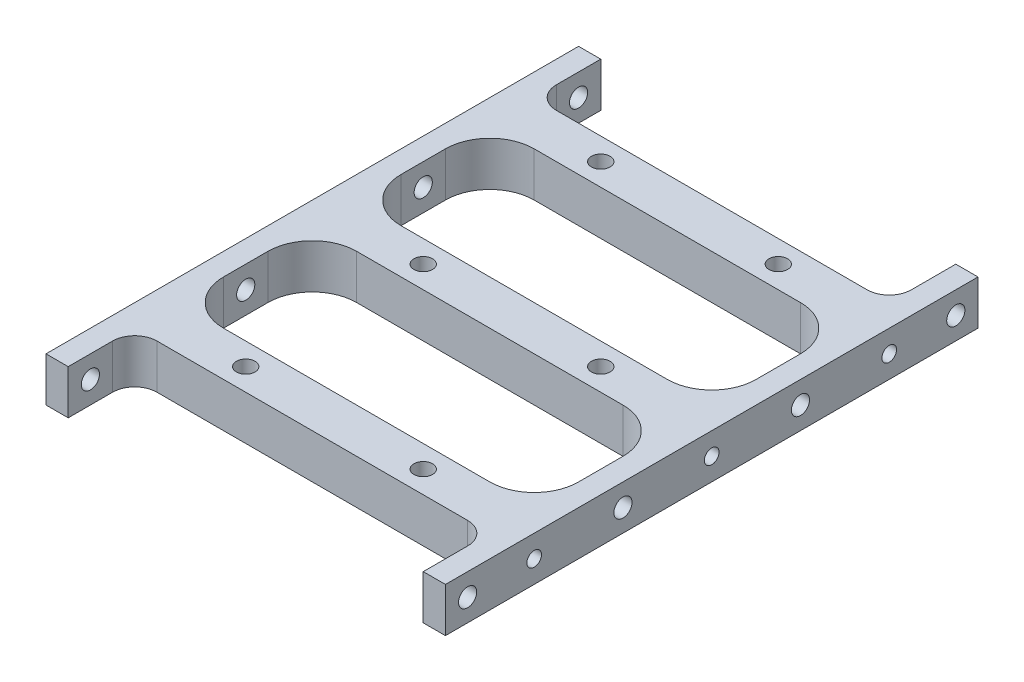
SolidWorks part; units mm, degrees
ref_plane "前视基准面" through (0, 0, 0) normal (0, 0, 1) x (1, 0, 0)
ref_plane "上视基准面" through (0, 0, 0) normal (0, 1, 0) x (1, 0, 0)
ref_plane "右视基准面" through (0, 0, 0) normal (1, 0, 0) x (0, 0, -1)
sketch "草图1" plane through (0, 0, 0) normal (0, 1, 0) x (1, 0, 0)
  line L0 (-45, 60) -> (-40, 60)
  line L1 (-40, 60) -> (-40, 45)
  line L2 (-30, 5) -> (30, 5)
  line L3 (40, 15) -> (40, 25)
  line L4 (40, 60) -> (45, 60)
  line L5 (45, 60) -> (45, -60)
  line L6 (45, -60) -> (40, -60)
  line L7 (40, -60) -> (40, -45)
  line L8 (30, -5) -> (-30, -5)
  line L9 (-40, -15) -> (-40, -25)
  line L10 (-40, -60) -> (-45, -60)
  line L11 (-45, -60) -> (-45, 60)
  line L12 (-45, 0) -> (45, 0) construction
  line L13 (0, 5) -> (0, -5) construction
  line L14 (-40, 45) -> (40, 45)
  line L15 (-30, 35) -> (30, 35)
  line L16 (-45, 40) -> (45, 40) construction
  line L17 (-45, -40) -> (45, -40) construction
  line L18 (-30, -35) -> (30, -35)
  line L19 (-40, -45) -> (40, -45)
  line L20 (-40, 25) -> (-40, 15)
  line L21 (40, 45) -> (40, 60)
  line L22 (40, -25) -> (40, -15)
  line L23 (-40, -45) -> (-40, -60)
  arc A0 (40, -25) -> (30, -35) centre (30, -25) cw
  arc A1 (-40, -25) -> (-30, -35) centre (-30, -25) ccw
  arc A2 (40, -15) -> (30, -5) centre (30, -15) ccw
  arc A3 (-40, -15) -> (-30, -5) centre (-30, -15) cw
  arc A4 (30, 5) -> (40, 15) centre (30, 15) ccw
  arc A5 (40, 25) -> (30, 35) centre (30, 25) ccw
  arc A6 (-40, 15) -> (-30, 5) centre (-30, 15) ccw
  arc A7 (-40, 25) -> (-30, 35) centre (-30, 25) cw
  point P31 (40, -35)
  point P46 (-40, 35)
  dimension "D10" = 10
  dimension "D1" = 90
  dimension "D2" = 10
  dimension "D3" = 5
  dimension "D4" = 5
  dimension "D5" = 120
  dimension "D6" = 40
  dimension "D7" = 10
  dimension "D8" = 40
  dimension "D9" = 10
extrude "凸台-拉伸1" add sketch "草图1" along normal mid plane 10
sketch "草图2" plane through (-45, 0, 0) normal (-1, 0, 0) x (0, 0, 1)
  line L0 (-55, 0) -> (55, 0) construction
  line L1 (-60, 5) -> (-60, -5) construction
  line L2 (60, 5) -> (60, -5) construction
  circle A0 centre (-55, 0) radius 2.05
  circle A1 centre (55, 0) radius 2.05
  circle A2 centre (-20, 0) radius 2.05
  circle A3 centre (20, 0) radius 2.05
  dimension "D1" = 5
  dimension "D2" = 35
  dimension "D3" = 5
  dimension "D4" = 35
  dimension "D5" = 4.1
extrude "切除-拉伸1" cut sketch "草图2" against normal through all
hole_wizard "M4 螺纹孔2" positions "草图7" profile "草图6" tap size "M4" standard "GB"
sketch "草图7" plane through (-45, 0, 0) normal (-1, 0, 0) x (0, 0, 1)
  circle A0 centre (-55, 0) radius 2.05 construction
  circle A1 centre (55, 0) radius 2.05 construction
  point P0 (0, 0)
  point P3 (-40, 0)
  point P8 (40, 0)
  dimension "D1" = 15
  dimension "D2" = 15
sketch "草图6" plane through (-45, 0, 0) normal (0, 1, 0) x (0, 0, 1)
  line L0 (0, 0) -> (0, 18.0914)
  line L1 (0, 18.0914) -> (1.65, 17.1)
  line L2 (1.65, 17.1) -> (1.65, 0)
  line L5 (1.65, 0) -> (0, 0)
  line L10 (0, 18.0914) -> (-1.65, 17.1) construction
  line L11 (0, -6.35) -> (0, 107.95) construction
  dimension "螺纹孔钻头直径" = 3.3
  dimension "螺纹孔钻头深度" = 17.1
  dimension "导头角度" = 118
cosmetic thread "孔螺蚊线4" parameters "D1"=12, "D2"=4
cosmetic thread "孔螺蚊线5" parameters "D1"=12, "D2"=4
cosmetic thread "孔螺蚊线6" parameters "D1"=12, "D2"=4
mirror "镜向1" about plane through (0, 0, 0) normal (1, 0, 0) of "M4 螺纹孔2"
fillet "圆角1" radius 5 4 edges at (-40, 0, 45) (40, 0, 45) (-40, 0, -45) (40, 0, -45)
hole_wizard "M5 螺纹孔1" positions "草图10" profile "草图9" tap size "M5" standard "GB" end condition through all
sketch "草图10" plane through (0, 5, 0) normal (0, 1, 0) x (1, 0, 0)
  line L0 (-20, 40) -> (20, 40) construction
  line L1 (20, 40) -> (20, 0) construction
  line L2 (20, 0) -> (20, -40) construction
  line L3 (20, -40) -> (-20, -40) construction
  line L4 (-20, -40) -> (-20, 0) construction
  line L5 (-20, 0) -> (-20, 40) construction
  line L7 (0, 0) -> (0, 40) construction
  point P2 (20, 40)
  point P4 (20, 0)
  point P6 (20, -40)
  point P8 (-20, -40)
  point P10 (-20, 0)
  point P12 (-20, 40)
  dimension "D1" = 40
  dimension "D2" = 40
  dimension "D3" = 20
sketch "草图9" plane through (20, 5, -40) normal (1, 0, 0) x (0, 0, 1)
  line L0 (0, 0) -> (0, 10)
  line L1 (0, 10) -> (2.1, 10)
  line L2 (2.1, 10) -> (2.1, 0)
  line L5 (2.1, 0) -> (0, 0)
  line L11 (0, -6.35) -> (0, 107.95) construction
  dimension "通孔螺纹孔钻头直径" = 4.2
  dimension "通孔螺纹孔钻头深度" = 10
cosmetic thread "孔螺蚊线7" parameters "D2"=5
cosmetic thread "孔螺蚊线8" parameters "D2"=5
cosmetic thread "孔螺蚊线9" parameters "D2"=5
cosmetic thread "孔螺蚊线10" parameters "D2"=5
cosmetic thread "孔螺蚊线11" parameters "D2"=5
cosmetic thread "孔螺蚊线12" parameters "D2"=5
